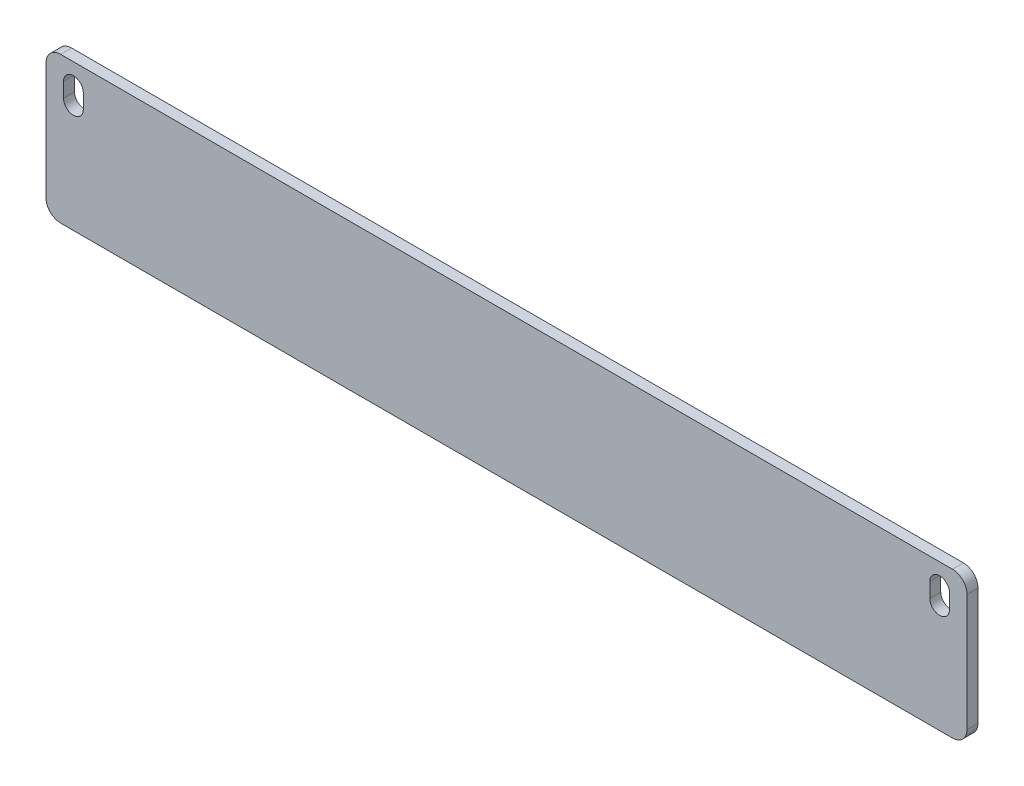
SolidWorks part; units mm, degrees
ref_plane "Front Plane" through (0, 0, 0) normal (0, 0, 1) x (1, 0, 0)
ref_plane "Top Plane" through (0, 0, 0) normal (0, 1, 0) x (1, 0, 0)
ref_plane "Right Plane" through (0, 0, 0) normal (1, 0, 0) x (0, 0, -1)
sketch "Sketch1" plane through (0, 0, 0) normal (0, 0, 1) x (1, 0, 0)
  line L0 (0, 34) -> (7.5, 34) construction
  line L1 (0, 0) -> (252, 0)
  line L2 (0, 0) -> (0, 40)
  line L3 (0, 40) -> (252, 40)
  line L4 (252, 0) -> (252, 40)
  line L5 (7.5, 34) -> (244.5, 34) construction
  line L6 (244.5, 34) -> (252, 34) construction
  line L7 (15, 32.8582) -> (15, 24.7198) construction
  line L8 (237, 23.4569) -> (237, 32.8582) construction
  line L9 (7.5, 34) -> (7.5, 30) construction
  line L10 (10.2, 34) -> (10.2, 30)
  line L11 (4.8, 34) -> (4.8, 30)
  line L12 (244.5, 34) -> (244.5, 30) construction
  line L13 (247.2, 34) -> (247.2, 30)
  line L14 (241.8, 34) -> (241.8, 30)
  arc A2 (10.2, 34) -> (4.8, 34) centre (7.5, 34) ccw
  arc A3 (4.8, 30) -> (10.2, 30) centre (7.5, 30) ccw
  arc A4 (247.2, 34) -> (241.8, 34) centre (244.5, 34) ccw
  arc A5 (241.8, 30) -> (247.2, 30) centre (244.5, 30) ccw
  point P6 (7.5, 32)
  point P19 (244.5, 32)
  dimension "D7" = 2.7
  dimension "D1" = 7.5
  dimension "D2" = 222
  dimension "D3" = 15
  dimension "D4" = 15
  dimension "D5" = 6
  dimension "D6" = 40
  dimension "D8" = 4
  dimension "D9" = 4
extrude "Boss-Extrude1" add sketch "Sketch1" along normal blind 3
sketch "Sketch2" plane through (0, 0, 0) normal (0, -1, 0) x (1, 0, 0)
  line L0 (16, 0) -> (16, -8)
  line L1 (16, -8) -> (236, -8)
  line L2 (236, -8) -> (236, 0)
  line L3 (0, 0) -> (252, 0) construction
  line L4 (236, 0) -> (16, 0)
  line L5 (0, 0) -> (16, 0) construction
  line L6 (236, 0) -> (252, 0) construction
  point P2 (236, -3)
  dimension "D1" = 220
  dimension "D2" = 8
extrude "Boss-Extrude2" add sketch "Sketch2" against normal blind 5
fillet "Fillet1" radius 4 4 edges at (252, 40, 1.5) (252, 0, 1.5) (0, 0, 1.5) (0, 40, 1.5)
fillet "Fillet2" radius 1 8 edges at (16, 2.5, 0) (236, 2.5, 0) (16, 5, -4) (126, 5, -8) (236, 5, -4) (126, 5, 0) (236, 2.5, -8) (16, 2.5, -8)
